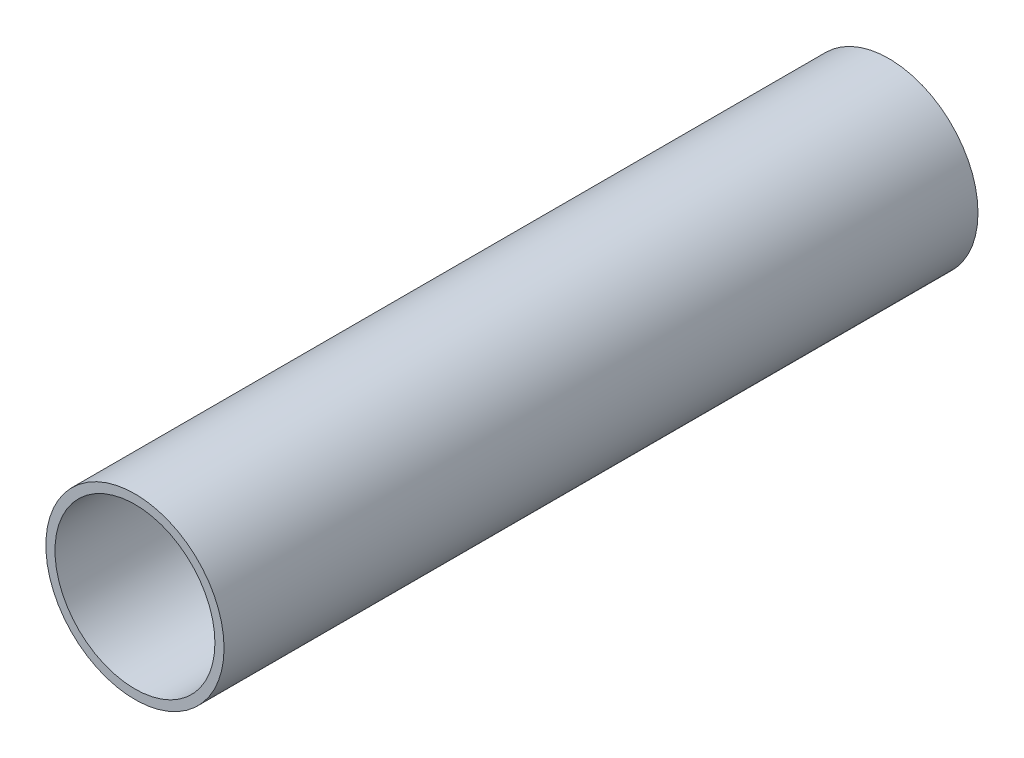
SolidWorks part; units mm, degrees
ref_plane "Front Plane" through (0, 0, 0) normal (0, 0, 1) x (1, 0, 0)
ref_plane "Top Plane" through (0, 0, 0) normal (0, 1, 0) x (1, 0, 0)
ref_plane "Right Plane" through (0, 0, 0) normal (1, 0, 0) x (0, 0, -1)
sketch "Sketch1" plane through (0, 0, 0) normal (0, 0, 1) x (1, 0, 0)
  circle A0 centre (0, 0) radius 1.75
  circle A1 centre (0, 0) radius 1.95
  dimension "D1" = 3.9
  dimension "D2" = 0.2
extrude "Boss-Extrude1" add sketch "Sketch1" along normal blind 16.5
